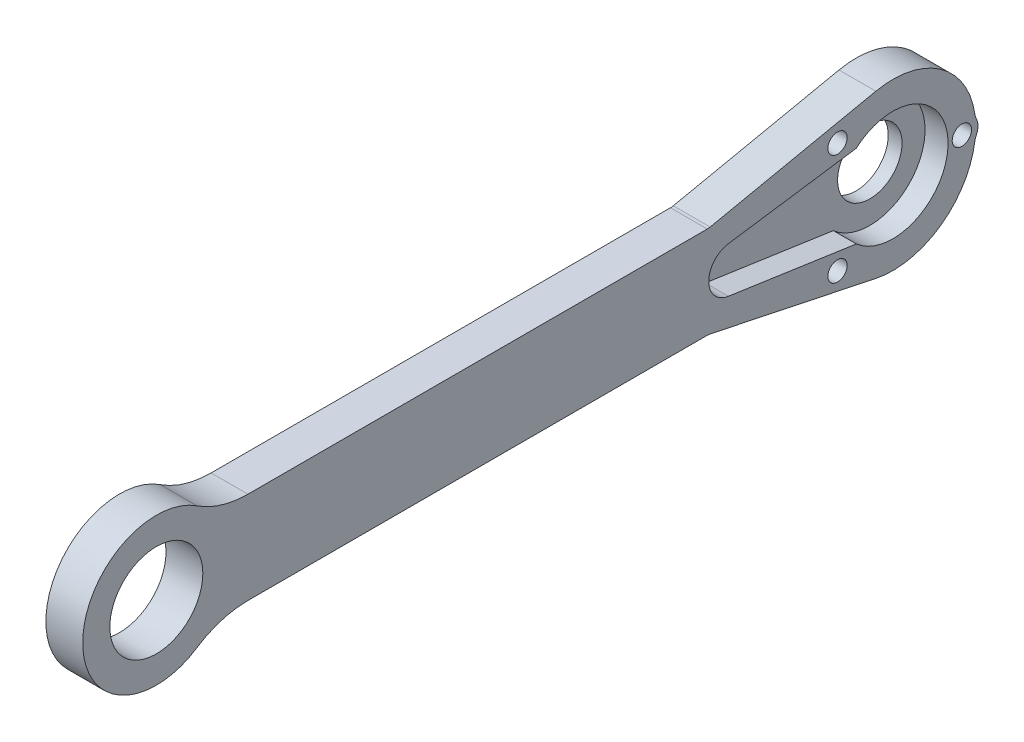
SolidWorks part; units mm, degrees
ref_plane "Plan de face" through (0, 0, 0) normal (0, 0, 1) x (1, 0, 0)
ref_plane "Plan de dessus" through (0, 0, 0) normal (0, 1, 0) x (1, 0, 0)
ref_plane "Plan de droite" through (0, 0, 0) normal (1, 0, 0) x (0, 0, -1)
sketch "Esquisse1" plane through (0, 0, 0) normal (1, 0, 0) x (0, 0, -1)
  line L0 (-47.7273, 0) -> (57.7273, 0) construction
  line L4 (0, 18.828) -> (0, -23.0645) construction
  line L7 (-33.755, 5) -> (20, 5)
  line L8 (-33.755, -5) -> (20, -5)
  line L9 (20, 12.9505) -> (20, -16.4973) construction
  line L10 (38.1521, 8.8082) -> (38.1521, -18.9143) construction
  line L11 (20, 5) -> (38.1521, 8.8082)
  line L12 (20, -5) -> (38.1521, -8.8082)
  circle A2 centre (-40, 0) radius 8 construction
  arc A3 (-33.755, 5) -> (-33.755, -5) centre (-40, 0) ccw
  arc A5 (38.1521, 8.8082) -> (38.1521, -8.8082) centre (40, 0) cw construction
  arc A8 (38.1521, -8.8082) -> (48.9458, -0.9859) centre (40, 0) ccw
  arc A9 (38.1521, 8.8082) -> (48.9458, 0.9859) centre (40, 0) cw
  circle A10 centre (47.5, 0) radius 1.75 construction
  arc A11 (48.9458, 0.9859) -> (48.9458, -0.9859) centre (47.5, 0) cw
  point P20 (0, -5)
  point P22 (0, 5)
  dimension "D3" = 10
  dimension "D4" = 9
  dimension "D6" = 3.5
  dimension "D5" = 7.5
  dimension "D7" = 40
  dimension "D1" = 8
  dimension "D2" = 80
  dimension "D8" = 20
extrude "Boss.-Extru.1" add sketch "Esquisse1" along normal blind 4
sketch "Esquisse2" plane through (4, 0, 0) normal (1, 0, 0) x (0, 0, -1)
  line L2 (38.1521, 8.8082) -> (20, 5)
  line L8 (20, 5) -> (-33.755, 5)
  line L9 (20, 5) -> (-33.755, 5)
  line L10 (-33.755, -5) -> (20, -5)
  line L11 (-33.755, -5) -> (20, -5)
  line L14 (38.1521, 8.8082) -> (20, 5)
  line L16 (20, -5) -> (38.1521, -8.8082)
  line L17 (20, -5) -> (38.1521, -8.8082)
  circle A0 centre (-40, 0) radius 5.05
  arc A2 (48.9458, 0.9859) -> (38.1521, 8.8082) centre (40, 0) ccw
  arc A3 (-33.755, 5) -> (-33.755, -5) centre (-40, 0) ccw
  arc A5 (-33.755, 5) -> (-33.755, -5) centre (-40, 0) ccw
  circle A6 centre (40, 0) radius 3.5
  arc A15 (48.9458, -0.9859) -> (48.9458, 0.9859) centre (47.5, 0) ccw
  arc A17 (48.9458, 0.9859) -> (38.1521, 8.8082) centre (40, 0) ccw
  arc A18 (38.1521, -8.8082) -> (48.9458, -0.9859) centre (40, 0) ccw
  arc A19 (38.1521, -8.8082) -> (48.9458, -0.9859) centre (40, 0) ccw
  arc A21 (48.9458, -0.9859) -> (48.9458, 0.9859) centre (47.5, 0) ccw
  dimension "D2" = 10.1
  dimension "D3" = 7
  dimension "D1" = 0
extrude "Enlèv. mat.-Extru.1" cut sketch "Esquisse2" against normal blind 10
sketch "Esquisse3" plane through (4, 0, 0) normal (1, 0, 0) x (0, 0, -1)
  line L0 (0, 0) -> (74.7488, 0) construction
  line L1 (38.1014, 11.1997) -> (38.1014, -12.7742) construction
  line L2 (38.1521, 8.8082) -> (20, 5)
  line L6 (23.0641, 4.5) -> (53.2637, 4.5) construction
  line L7 (0, 17.2639) -> (0, -16.0675) construction
  line L8 (30.5083, 6.6344) -> (30.5083, -6.2819) construction
  line L9 (22.1392, 2.4738) -> (36.0314, 4.5)
  line L10 (22.1392, -2.4738) -> (36.0314, -4.5)
  line L15 (20, 5) -> (-33.755, 5)
  line L16 (20, 5) -> (-33.755, 5)
  line L17 (-33.755, -5) -> (20, -5)
  line L18 (-33.755, -5) -> (20, -5)
  line L21 (38.1521, 8.8082) -> (20, 5)
  line L23 (20, -5) -> (38.1521, -8.8082)
  line L24 (20, -5) -> (38.1521, -8.8082)
  circle A0 centre (40, 0) radius 6 construction
  circle A1 centre (22.5, 0) radius 2.5 construction
  arc A2 (48.9458, 0.9859) -> (38.1521, 8.8082) centre (40, 0) ccw
  arc A3 (-33.755, 5) -> (-33.755, -5) centre (-40, 0) ccw
  arc A5 (-33.755, 5) -> (-33.755, -5) centre (-40, 0) ccw
  arc A6 (22.1392, -2.4738) -> (22.1392, 2.4738) centre (22.5, 0) cw
  arc A7 (36.0314, -4.5) -> (36.0314, 4.5) centre (40, 0) ccw
  arc A16 (48.9458, -0.9859) -> (48.9458, 0.9859) centre (47.5, 0) ccw
  arc A18 (48.9458, 0.9859) -> (38.1521, 8.8082) centre (40, 0) ccw
  arc A19 (38.1521, -8.8082) -> (48.9458, -0.9859) centre (40, 0) ccw
  arc A20 (38.1521, -8.8082) -> (48.9458, -0.9859) centre (40, 0) ccw
  arc A22 (48.9458, -0.9859) -> (48.9458, 0.9859) centre (47.5, 0) ccw
  dimension "D2" = 12
  dimension "D4" = 17.5
  dimension "D5" = 5
  dimension "D3" = 4.5
  dimension "D1" = 0
extrude "Enlèv. mat.-Extru.2" cut sketch "Esquisse3" against normal blind 2.5 contours A7 L9 A6 L10
sketch "Esquisse5" plane through (4, 0, 0) normal (1, 0, 0) x (0, 0, -1)
  line L0 (0, 16.8077) -> (0, -27.9422) construction
  line L1 (-64.0496, 0) -> (62.7771, 0) construction
  line L2 (22.1392, -2.4738) -> (36.0314, -4.5)
  line L3 (36.0314, 4.5) -> (22.1392, 2.4738)
  line L4 (22.1392, -2.4738) -> (36.0314, -4.5)
  line L5 (36.0314, 4.5) -> (22.1392, 2.4738)
  line L6 (40, 0) -> (29.0152, 10.9848) construction
  line L8 (38.1521, 8.8082) -> (20, 5)
  line L9 (20, 5) -> (-33.755, 5)
  line L10 (-33.755, -5) -> (20, -5)
  line L13 (20, 5) -> (-33.755, 5)
  line L14 (-33.755, -5) -> (20, -5)
  line L18 (38.1521, 8.8082) -> (20, 5)
  line L20 (20, -5) -> (38.1521, -8.8082)
  line L21 (20, -5) -> (38.1521, -8.8082)
  arc A2 (36.0314, -4.5) -> (36.0314, 4.5) centre (40, 0) ccw
  arc A3 (22.1392, 2.4738) -> (22.1392, -2.4738) centre (22.5, 0) ccw
  arc A4 (36.0314, -4.5) -> (36.0314, 4.5) centre (40, 0) ccw
  arc A5 (22.1392, 2.4738) -> (22.1392, -2.4738) centre (22.5, 0) ccw
  arc A6 (48.9458, 0.9859) -> (38.1521, 8.8082) centre (40, 0) ccw
  arc A7 (-33.755, 5) -> (-33.755, -5) centre (-40, 0) ccw
  arc A9 (-33.755, 5) -> (-33.755, -5) centre (-40, 0) ccw
  circle A10 centre (40, 0) radius 8.5 construction
  circle A11 centre (33.9896, 6.0104) radius 1.05
  circle A12 centre (33.9896, -6.0104) radius 1.05
  circle A13 centre (47.5, 0) radius 1.05
  arc A17 (48.9458, -0.9859) -> (48.9458, 0.9859) centre (47.5, 0) ccw
  arc A22 (48.9458, 0.9859) -> (38.1521, 8.8082) centre (40, 0) ccw
  arc A23 (38.1521, -8.8082) -> (48.9458, -0.9859) centre (40, 0) ccw
  arc A24 (38.1521, -8.8082) -> (48.9458, -0.9859) centre (40, 0) ccw
  arc A26 (48.9458, -0.9859) -> (48.9458, 0.9859) centre (47.5, 0) ccw
  dimension "D3" = 2.1
  dimension "D4" = 17
  dimension "D5" = 45
  dimension "D1" = 0
  dimension "D2" = 0
extrude "Enlèv. mat.-Extru.3" cut sketch "Esquisse5" against normal through all
fillet "Congé2" radius 1.5 4 edges at (2, 0.9859, -48.9458) (2, -0.9859, -48.9458) (2, 5, -20) (2, -5, -20)
fillet "Congé3" radius 10 2 edges at (2, -5, 33.755) (2, 5, 33.755)
